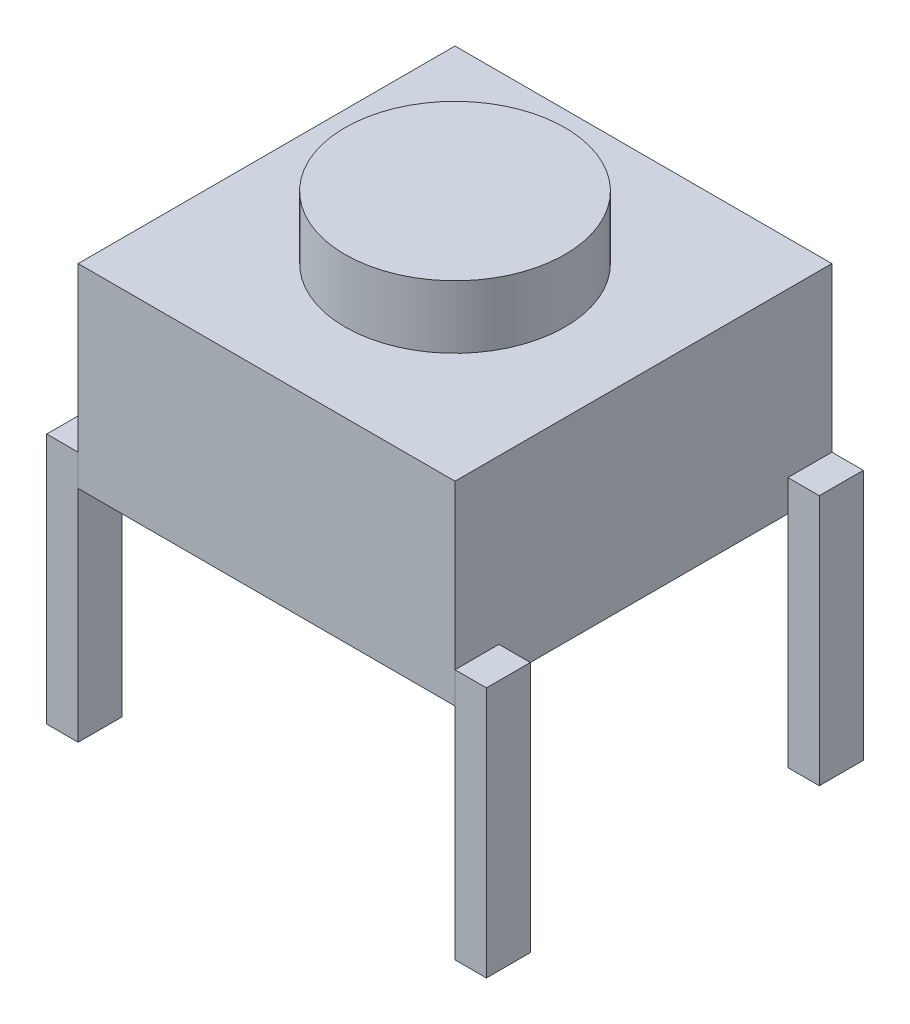
SolidWorks part; units mm, degrees
ref_plane "Front Plane" through (0, 0, 0) normal (0, 0, 1) x (1, 0, 0)
ref_plane "Top Plane" through (0, 0, 0) normal (0, 1, 0) x (1, 0, 0)
ref_plane "Right Plane" through (0, 0, 0) normal (1, 0, 0) x (0, 0, -1)
sketch "Sketch1" plane through (0, 0, 0) normal (0, 1, 0) x (1, 0, 0)
  line L1 (-3, 3) -> (3, 3)
  line L2 (-3, 3) -> (-3, -3)
  line L3 (-3, -3) -> (3, -3)
  line L4 (3, 3) -> (3, -3)
  point P4 (0, 3)
  point P6 (-3, 0)
  dimension "D1" = 6
extrude "Boss-Extrude1" add sketch "Sketch1" along normal blind 3.1
sketch "Sketch2" plane through (0, 3.1, 0) normal (0, 1, 0) x (1, 0, 0)
  circle A0 centre (0, 0) radius 1.75
  dimension "D1" = 3.5
extrude "Boss-Extrude2" add sketch "Sketch2" along normal blind 1
sketch "Sketch3" plane through (0, 0, 3) normal (0, 0, 1) x (1, 0, 0)
  line L0 (0, 0) -> (0, 3.1) construction
  line L1 (-3, 0) -> (3, 0) construction
  line L2 (-3, 3.1) -> (3, 3.1) construction
  line L3 (3, 3.1) -> (3, 0) construction
  line L4 (3, 0.5) -> (3.5, 0.5)
  line L5 (3, 0.5) -> (3, -3.5)
  line L6 (3, -3.5) -> (3.5, -3.5)
  line L7 (3.5, 0.5) -> (3.5, -3.5)
  line L8 (-3.5, 0.5) -> (-3.5, -3.5)
  line L9 (-3, -3.5) -> (-3.5, -3.5)
  line L10 (-3, 0.5) -> (-3, -3.5)
  line L11 (-3, 0.5) -> (-3.5, 0.5)
  dimension "D1" = 4
  dimension "D2" = 0.5
  dimension "D3" = 0.5
extrude "Boss-Extrude3" add sketch "Sketch3" against normal blind 0.7 separate body
sketch "Sketch4" plane through (0, 0, -3) normal (0, 0, -1) x (-1, 0, 0)
  line L1 (-3, 0.5) -> (-3.5, 0.5)
  line L2 (-3, 0.5) -> (-3, -3.5)
  line L3 (-3, -3.5) -> (-3.5, -3.5)
  line L4 (-3.5, 0.5) -> (-3.5, -3.5)
  line L5 (3, 0.5) -> (3.5, 0.5)
  line L6 (3, 0.5) -> (3, -3.5)
  line L7 (3, -3.5) -> (3.5, -3.5)
  line L8 (3.5, 0.5) -> (3.5, -3.5)
extrude "Boss-Extrude4" add sketch "Sketch4" against normal blind 0.7 separate body
